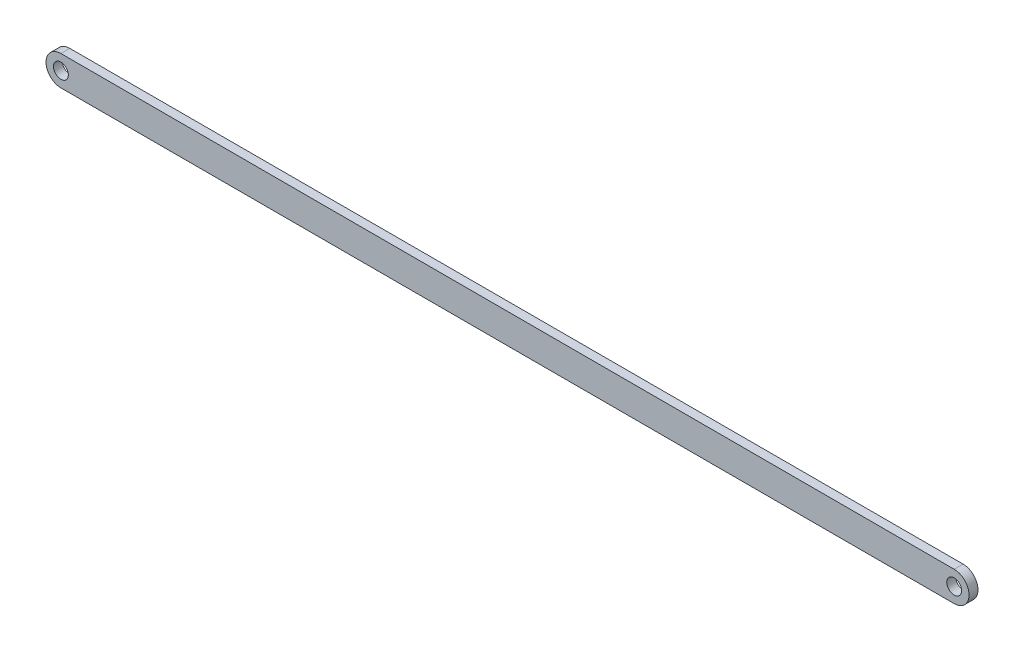
SolidWorks part; units mm, degrees
ref_plane "Front Plane" through (0, 0, 0) normal (0, 0, 1) x (1, 0, 0)
ref_plane "Top Plane" through (0, 0, 0) normal (0, 1, 0) x (1, 0, 0)
ref_plane "Right Plane" through (0, 0, 0) normal (1, 0, 0) x (0, 0, -1)
sketch "Sketch1" plane through (0, 0, 0) normal (0, 0, 1) x (1, 0, 0)
  line L0 (-150, 0) -> (150, 0) construction
  line L1 (-150, 5) -> (150, 5)
  line L2 (-150, -5) -> (150, -5)
  arc A0 (-150, 5) -> (-150, -5) centre (-150, 0) ccw
  arc A1 (150, -5) -> (150, 5) centre (150, 0) ccw
  point P2 (0, 0)
  dimension "D1" = 300
  dimension "D2" = 10
extrude "Boss-Extrude1" add sketch "Sketch1" along normal blind 3
sketch "Sketch2" plane through (0, 0, 3) normal (0, 0, 1) x (1, 0, 0)
  circle A0 centre (-150, 0) radius 2.5
  dimension "D1" = 5
extrude "Cut-Extrude1" cut sketch "Sketch2" against normal up to next
mirror "Mirror1" about plane through (0, 0, 0) normal (1, 0, 0) of "Cut-Extrude1"
sketch "Sketch4" [suppressed] plane through (0, 0, 3) normal (0, 0, 1) x (1, 0, 0)
  circle A0 centre (-70, 0) radius 5
  arc A1 (130, -10) -> (130, 10) centre (130, 0) ccw construction
  point P5 (140, 0)
  dimension "D1" = 5
  dimension "D2" = 210
extrude "Cut-Extrude3" [suppressed] cut sketch "Sketch4" against normal up to next
